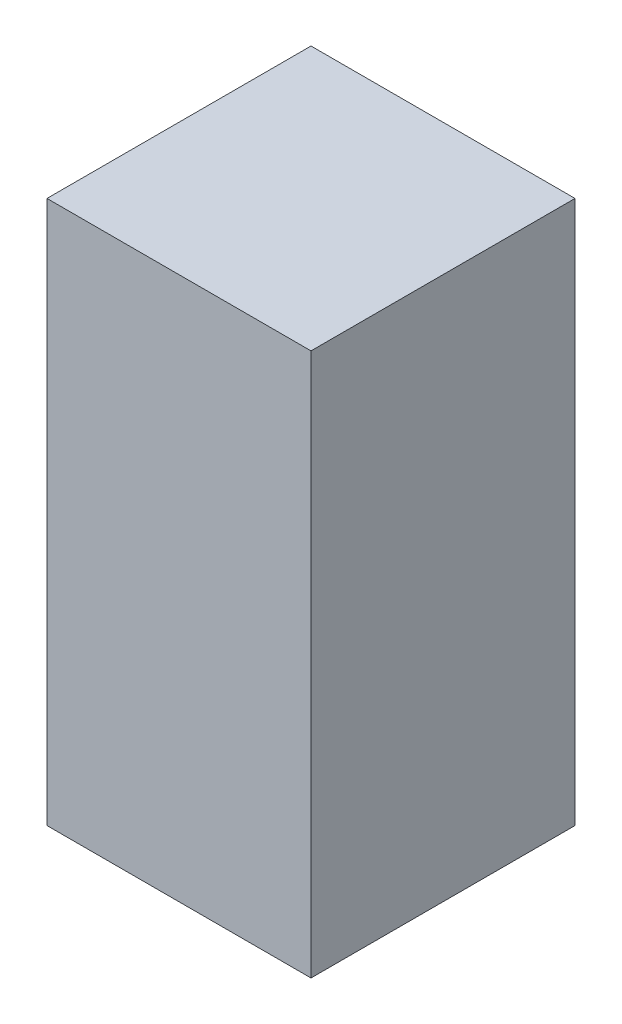
SolidWorks part; units mm, degrees
ref_plane "Plan de face" through (0, 0, 0) normal (0, 0, 1) x (1, 0, 0)
ref_plane "Plan de dessus" through (0, 0, 0) normal (0, 1, 0) x (1, 0, 0)
ref_plane "Plan de droite" through (0, 0, 0) normal (1, 0, 0) x (0, 0, -1)
sketch "Esquisse1" plane through (0, 0, 0) normal (0, 0, 1) x (1, 0, 0)
  line L1 (17.5, -36) -> (-17.5, -36)
  line L2 (17.5, -36) -> (17.5, 36)
  line L3 (17.5, 36) -> (-17.5, 36)
  line L4 (-17.5, -36) -> (-17.5, 36)
  line L5 (17.5, -36) -> (-17.5, 36) construction
  line L6 (17.5, 36) -> (-17.5, -36) construction
  point P0 (0, 0)
  dimension "D1" = 72
  dimension "D2" = 35
extrude "Boss.-Extru.1" add sketch "Esquisse1" along normal blind 35
